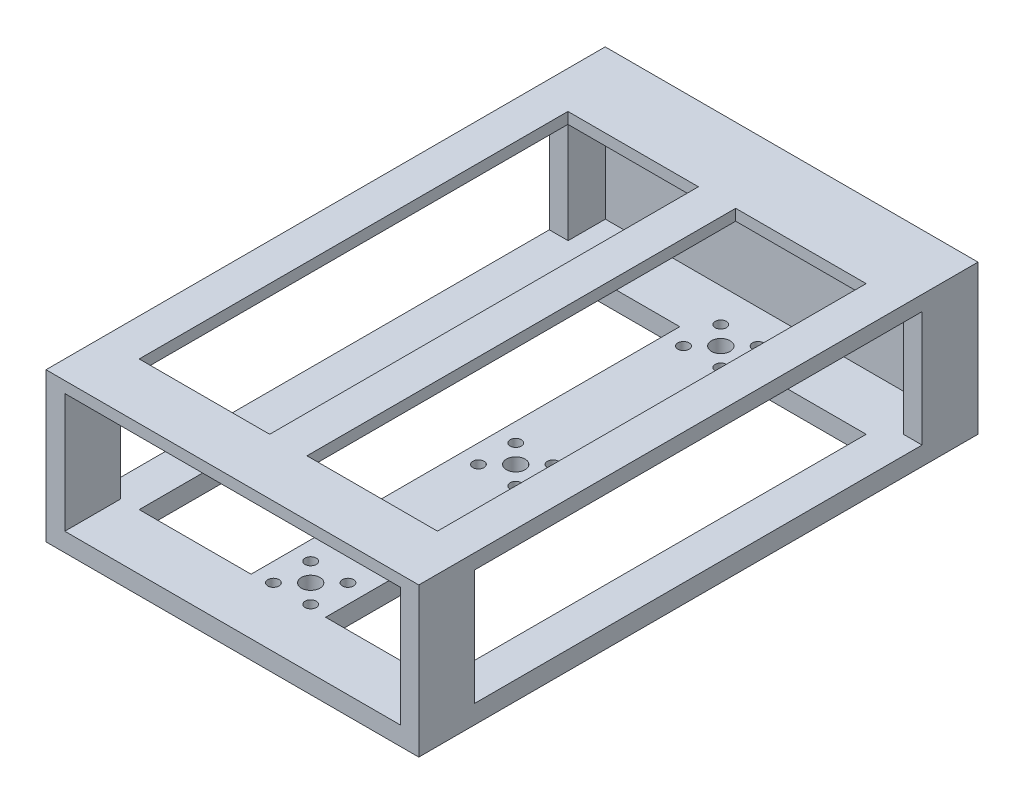
SolidWorks part; units mm, degrees
ref_plane "Front" through (0, 0, 0) normal (0, 0, 1) x (1, 0, 0)
ref_plane "Top" through (0, 0, 0) normal (0, 1, 0) x (1, 0, 0)
ref_plane "Right" through (0, 0, 0) normal (1, 0, 0) x (0, 0, -1)
sketch "草图2" plane through (0, 0, 0) normal (0, 0, 1) x (1, 0, 0)
  line L1 (-50, 20) -> (50, 20)
  line L2 (-50, 20) -> (-50, -20)
  line L3 (-50, -20) -> (50, -20)
  line L4 (50, 20) -> (50, -20)
  line L5 (-50, 20) -> (50, -20) construction
  line L6 (-50, -20) -> (50, 20) construction
  point P0 (0, 0)
  dimension "D1" = 100
  dimension "D2" = 40
extrude "凸台-拉伸1" add sketch "草图2" along normal blind 150
sketch "草图3" plane through (0, 0, 150) normal (0, 0, 1) x (1, 0, 0)
  line L0 (50, 20) -> (-50, 20) construction
  line L1 (-44.9554, 17) -> (45.0446, 17)
  line L2 (-44.9554, 17) -> (-44.9554, -15)
  line L3 (-44.9554, -15) -> (45.0446, -15)
  line L4 (45.0446, 17) -> (45.0446, -15)
  line L8 (-50, -20) -> (50, -20) construction
  point P0 (0, 0)
  dimension "D1" = 90
  dimension "D2" = 3
  dimension "D3" = 5
extrude "切除-拉伸1" cut sketch "草图3" against normal blind 145
sketch "草图4" plane through (0, -20, 0) normal (0, -1, 0) x (1, 0, 0)
  line L0 (-50, 150) -> (50, 150) construction
  line L1 (-40, 135) -> (-10, 135)
  line L2 (-40, 135) -> (-40, 20)
  line L3 (-40, 20) -> (-10, 20)
  line L4 (-10, 135) -> (-10, 20)
  line L5 (10, 135) -> (40, 135)
  line L6 (10, 135) -> (10, 20)
  line L7 (10, 20) -> (40, 20)
  line L8 (40, 135) -> (40, 20)
  line L9 (-50, 0) -> (50, 0) construction
  line L10 (-50, 150) -> (-50, 0) construction
  line L11 (50, 150) -> (50, 0) construction
  dimension "D1" = 15
  dimension "D2" = 20
  dimension "D3" = 20
  dimension "D4" = 15
  dimension "D5" = 10
  dimension "D6" = 10
  dimension "D7" = 30
  dimension "D8" = 30
extrude "切除-拉伸2" cut sketch "草图4" against normal blind 20
sketch "草图5" plane through (0, 20, 0) normal (0, 1, 0) x (1, 0, 0)
  line L0 (50, 0) -> (-50, 0) construction
  line L1 (-40, -20) -> (-5, -20)
  line L2 (-40, -20) -> (-40, -135)
  line L3 (-40, -135) -> (-5, -135)
  line L4 (-5, -20) -> (-5, -135)
  line L5 (5, -20) -> (40, -20)
  line L6 (5, -20) -> (5, -135)
  line L7 (5, -135) -> (40, -135)
  line L8 (40, -20) -> (40, -135)
  line L9 (-50, -150) -> (-50, 0) construction
  line L10 (50, -150) -> (50, 0) construction
  line L11 (50, -150) -> (-50, -150) construction
  dimension "D1" = 20
  dimension "D2" = 20
  dimension "D3" = 10
  dimension "D4" = 10
  dimension "D5" = 15
  dimension "D6" = 15
  dimension "D7" = 35
  dimension "D8" = 35
extrude "切除-拉伸3" cut sketch "草图5" against normal blind 20
sketch "草图6" plane through (-50, 0, 0) normal (-1, 0, 0) x (0, 0, 1)
  line L0 (150, 20) -> (0, 20) construction
  line L1 (15, 16) -> (135, 16)
  line L2 (15, 16) -> (15, -15)
  line L3 (15, -15) -> (135, -15)
  line L4 (135, 16) -> (135, -15)
  line L5 (150, -20) -> (0, -20) construction
  line L6 (150, 20) -> (150, -20) construction
  line L7 (0, 20) -> (0, -20) construction
  dimension "D1" = 4
  dimension "D2" = 5
  dimension "D3" = 15
  dimension "D4" = 15
extrude "切除-拉伸4" cut sketch "草图6" against normal blind 207
sketch "草图7" plane through (0, -20, 0) normal (0, -1, 0) x (1, 0, 0)
  line L1 (-10, 20) -> (-10, 135) construction
  line L2 (-50, 150) -> (50, 150) construction
  circle A0 centre (-5, 134) radius 1.5
  circle A1 centre (5, 134) radius 1.5
  circle A2 centre (5, 124) radius 1.5
  circle A3 centre (-5, 124) radius 1.5
  dimension "D1" = 3
  dimension "D2" = 3
  dimension "D3" = 3
  dimension "D4" = 3
  dimension "D5" = 10
  dimension "D6" = 10
  dimension "D7" = 10
  dimension "D8" = 5
  dimension "D9" = 5
  dimension "D10" = 16
  dimension "D11" = 16
  dimension "D12" = 10
extrude "切除-拉伸5" cut sketch "草图7" against normal blind 15
sketch "草图8" plane through (0, -20, 0) normal (0, -1, 0) x (1, 0, 0)
  circle A0 centre (0, 129) radius 2.5
  circle A1 centre (5, 134) radius 1.5 construction
  circle A2 centre (0, 74) radius 2.5
  circle A3 centre (0, 19) radius 2.5
  circle A4 centre (-5, 79) radius 1.5
  circle A5 centre (-5, 69) radius 1.5
  circle A6 centre (5, 69) radius 1.5
  circle A7 centre (5, 79) radius 1.5
  circle A8 centre (-5, 14) radius 1.5
  circle A9 centre (-5, 24) radius 1.5
  circle A10 centre (5, 24) radius 1.5
  circle A11 centre (5, 14) radius 1.5
  point P24 (0, 0)
  point P25 (0, 0)
  point P26 (0, 0)
  point P27 (0, 0)
  point P28 (0, 0)
  point P29 (0, 0)
  point P30 (0, 0)
  point P31 (0, 0)
  dimension "D1" = 5
  dimension "D3" = 5
  dimension "D4" = 5
  dimension "D6" = 55
  dimension "D9" = 3
  dimension "D10" = 3
  dimension "D11" = 3
  dimension "D12" = 3
  dimension "D18" = 3
  dimension "D19" = 3
  dimension "D20" = 3
  dimension "D21" = 3
  dimension "D2" = 5
  dimension "D5" = 55
  dimension "D7" = 10
  dimension "D8" = 10
  dimension "D13" = 10
  dimension "D14" = 5
  dimension "D15" = 5
  dimension "D16" = 5
  dimension "D17" = 5
  dimension "D22" = 10
  dimension "D23" = 10
extrude "切除-拉伸6" cut sketch "草图8" against normal blind 15
